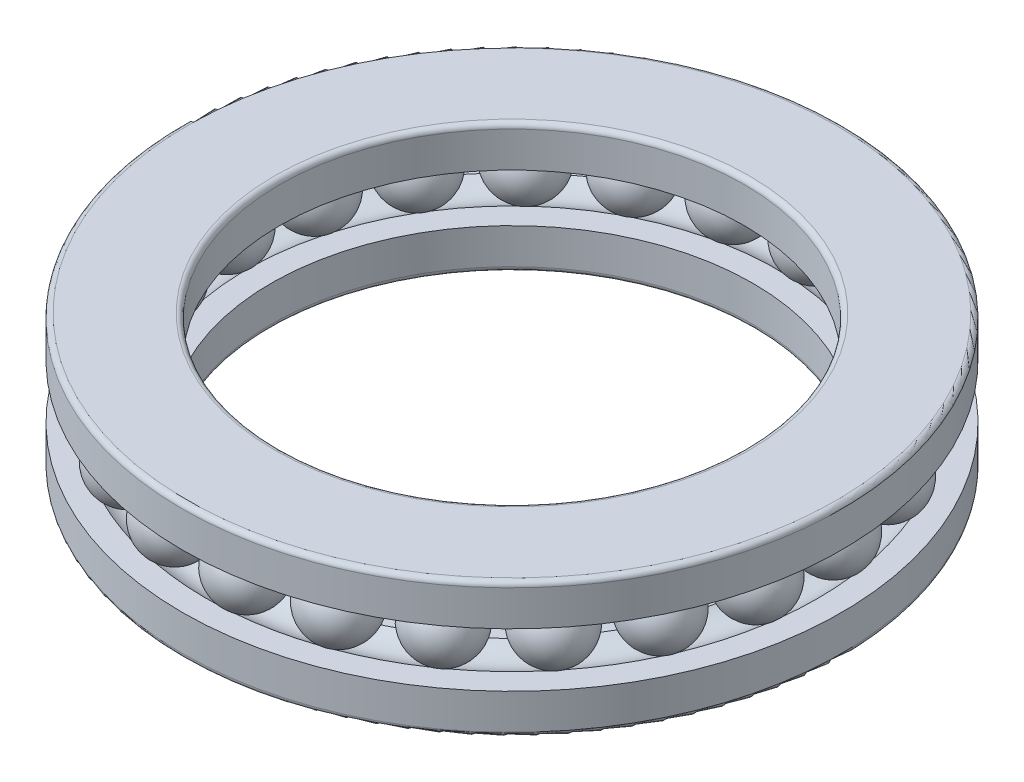
SolidWorks part; units mm, degrees
material "AISI 304"
ref_plane "基准面1" through (0, 0, 0) normal (0, 0, 1) x (1, 0, 0)
ref_plane "基准面2" through (0, 0, 0) normal (0, 1, 0) x (1, 0, 0)
ref_plane "基准面3" through (0, 0, 0) normal (1, 0, 0) x (0, 0, -1)
sketch "尺寸草图" plane through (0, 0, 0) normal (0, 0, 1) x (1, 0, 0)
  line L0 (0, 0) -> (78, 0)
  point P3 (55, 0)
  point P4 (57, 0)
  point P5 (78, 0)
  point P6 (16, 0)
  point P7 (0.6, 0)
  dimension "DD" = 78
  dimension "d" = 55
  dimension "d1" = 57
  dimension "DD1" = 78
  dimension "T" = 16
  dimension "r" = 0.6
sketch "草图1" plane through (0, 0, 0) normal (0, 0, 1) x (1, 0, 0)
  line L0 (39, 0) -> (39, 37.489) construction
  line L1 (0, 0) -> (78, 0)
  line L2 (0, 0) -> (0, 16)
  line L3 (0, 16) -> (78, 16)
  line L4 (78, 0) -> (78, 16)
  line L5 (11.5, 0) -> (11.5, 16)
  line L6 (66.5, 0) -> (66.5, 11.2)
  line L7 (0, 0) -> (0, 16)
  line L8 (78, 0) -> (78, 16)
  line L9 (10.5, 0) -> (10.5, 16)
  line L10 (67.5, 0) -> (67.5, 16)
  line L11 (0, 8) -> (78, 8) construction
  line L12 (72.75, 0) -> (72.75, 16)
  line L13 (5.25, 0) -> (5.25, 16)
  line L14 (0, 4.8) -> (78, 4.8)
  line L15 (0, 11.2) -> (78, 11.2)
  circle A0 centre (5.25, 8) radius 4
  dimension "D8" = 8
  dimension "D1" = 78
  dimension "D2" = 16
  dimension "D3" = 78
  dimension "D4" = 55
  dimension "D5" = 57
  dimension "D6" = 67.5
  dimension "D7" = 6.4
sketch "草图2" plane through (0, 0, 0) normal (0, 0, 1) x (1, 0, 0)
  line L0 (0, 4.8) -> (78, 4.8) construction
  line L1 (39, 0) -> (39, 37.489) construction
  line L2 (10.5, 0) -> (10.5, 16) construction
  line L3 (0, 4.8) -> (2.85, 4.8)
  line L4 (0, 0) -> (78, 0)
  line L5 (78, 0) -> (78, 16)
  line L6 (78, 16) -> (0, 16)
  line L7 (0, 16) -> (0, 0)
  line L8 (0, 0) -> (10.5, 0)
  line L9 (7.65, 4.8) -> (10.5, 4.8)
  line L11 (0, 4.8) -> (0, 0)
  line L12 (39, 0) -> (39, 37.489) construction
  line L13 (10.5, 0) -> (10.5, 4.8)
  circle A0 centre (5.25, 8) radius 4 construction
  arc A1 (2.85, 4.8) -> (7.65, 4.8) centre (5.25, 8) ccw
  dimension "D1" = 0
revolve "基体-旋转" add sketch "草图2" angle 360 about L12
sketch "草图3" plane through (0, 0, 0) normal (0, 0, 1) x (1, 0, 0)
  line L2 (5.25, 0) -> (5.25, 16) construction
  line L3 (5.25, 0) -> (5.25, 16) construction
  line L4 (5.25, 3.95) -> (5.25, 12.05)
  circle A0 centre (5.25, 8) radius 4 construction
  arc A1 (5.25, 12) -> (5.25, 4) centre (5.25, 8) ccw construction
  arc A2 (5.25, 12.05) -> (5.25, 3.95) centre (5.25, 8) ccw
  dimension "D1" = 0.05
revolve "凸台-旋转2" add sketch "草图3" angle 360 about L3
sketch "草图4" plane through (0, 0, 0) normal (0, 0, 1) x (1, 0, 0)
  line L0 (39, 0) -> (39, 37.489) construction
  line L1 (0, 11.2) -> (78, 11.2) construction
  line L2 (11.5, 0) -> (11.5, 16) construction
  line L3 (0, 0) -> (0, 16) construction
  line L4 (0, 16) -> (78, 16) construction
  line L5 (39, 0) -> (39, 37.489) construction
  line L6 (0, 11.2) -> (2.85, 11.2)
  line L7 (11.5, 11.2) -> (11.5, 16)
  line L8 (0, 11.2) -> (0, 16)
  line L9 (0, 16) -> (11.5, 16)
  line L12 (7.65, 11.2) -> (11.5, 11.2)
  circle A0 centre (5.25, 8) radius 4 construction
  arc A1 (7.65, 11.2) -> (2.85, 11.2) centre (5.25, 8) ccw
revolve "凸台-旋转3" add sketch "草图4" angle 360 about L5
pattern_circular "阵列(圆周)1" count 23 over 360 about axis through (39, 0, 0) along (0, 1, 0) of "凸台-旋转2"
fillet "圆角1" radius 0.6 4 edges at (39, 16, -27.5) (39, 16, -39) (39, 0, -28.5) (39, 0, -39)
